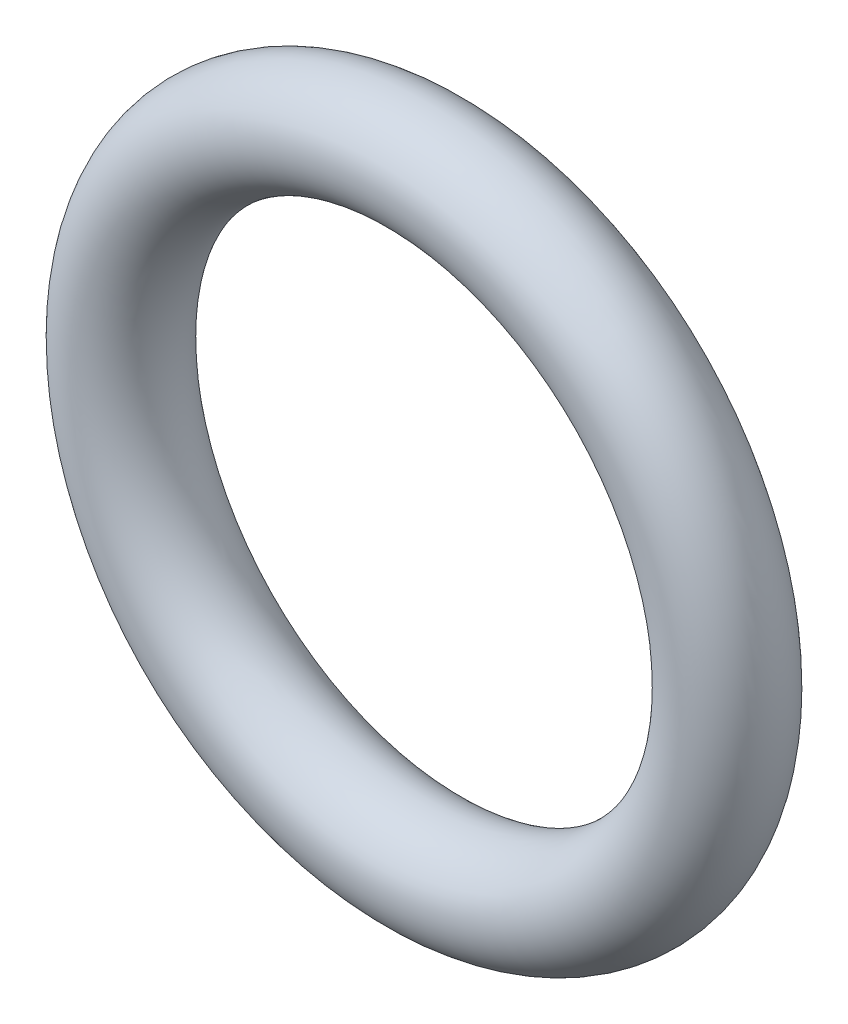
SolidWorks part; units mm, degrees
ref_plane "Front" through (0, 0, 0) normal (0, 0, 1) x (1, 0, 0)
ref_plane "Top" through (0, 0, 0) normal (0, 1, 0) x (1, 0, 0)
ref_plane "Right" through (0, 0, 0) normal (1, 0, 0) x (0, 0, -1)
sketch "Sketch1" plane through (0, 0, 0) normal (1, 0, 0) x (0, -1, 0)
  line L0 (0, -1.3081) -> (0, 1.3081) construction
  line L2 (-9.6812, 0) -> (9.6812, 0) construction
  line L3 (-6.1849, 0) -> (6.1849, 0) construction
  circle A0 centre (7.493, 0) radius 1.3081
  point P9 (6.1849, 0)
  point P10 (8.8011, 0)
  point P13 (7.493, 1.3081)
  point P14 (7.493, -1.3081)
  dimension "Width" = 2.6162
  dimension "ID" = 12.3698
revolve "Revolve1" add sketch "Sketch1" angle 360 about L0
ref_plane "Plane1" through (0, -7.493, 1.3081) normal (0, 0, 1) x (1, 0, 0)
sketch "Sketch2" plane through (0, -7.493, 1.3081) normal (0, 0, 1) x (1, 0, 0)
  circle A0 centre (0, 7.493) radius 7.493
